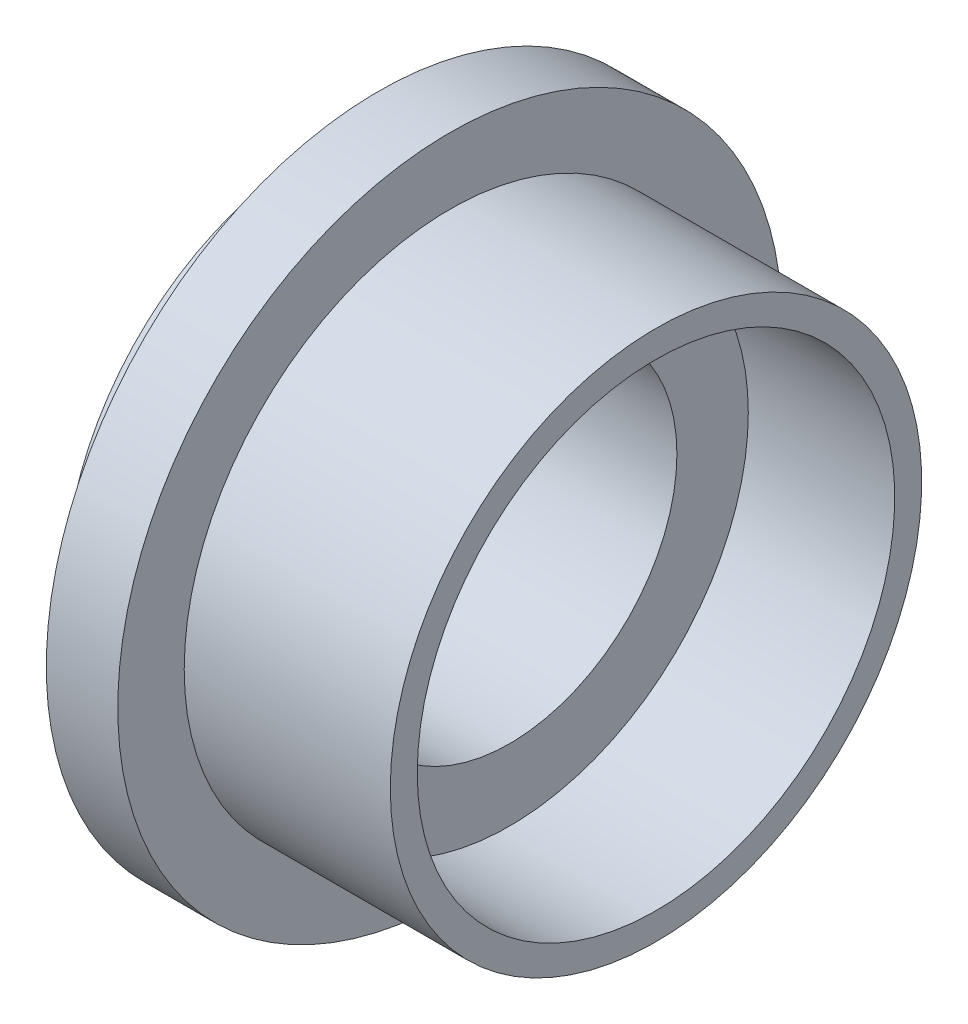
SolidWorks part; units mm, degrees
ref_plane "Front Plane" through (0, 0, 0) normal (0, 0, 1) x (1, 0, 0)
ref_plane "Top Plane" through (0, 0, 0) normal (0, 1, 0) x (1, 0, 0)
ref_plane "Right Plane" through (0, 0, 0) normal (1, 0, 0) x (0, 0, -1)
sketch "Sketch1" plane through (0, 0, 0) normal (0, 0, 1) x (1, 0, 0)
  line L0 (-3.5, 8) -> (-3.5, 11.412)
  line L1 (-3.5, 11.412) -> (-3.5, -9.888) construction
  line L2 (-3.5, 11.412) -> (-6.35, 11.412)
  line L3 (-6.35, 19.05) -> (-6.35, -19.05) construction
  line L4 (-6.35, 11.412) -> (-6.35, 15.875)
  line L5 (-6.35, 15.875) -> (-9.7671, 15.875)
  line L6 (-9.7671, 15.875) -> (-11.6001, 12.7)
  line L7 (-12.7, 12.065) -> (-22.904, 12.065) construction
  line L8 (-12.7, 12.065) -> (-12.7, 8)
  line L9 (-12.7, 8) -> (-3.5, 8)
  line L10 (0, 0) -> (-17.096, 0) construction
  arc A0 (-11.6001, 12.7) -> (-12.7, 12.065) centre (-12.7, 13.335) cw
  dimension "D1" = 15.875
  dimension "D3" = 1.27
  dimension "D2" = 8
  dimension "D4" = 6.35
  dimension "D5" = 60
  dimension "D6" = 3.81
revolve "Revolve1" add sketch "Sketch1" angle 360 about L10
sketch "Sketch2" plane through (-6.35, 0, 0) normal (1, 0, 0) x (0, 0, -1)
  circle A1 centre (0, 0) radius 12.7
  circle A2 centre (0, 0) radius 11.412
  circle A3 centre (0, 0) radius 11.412 construction
  dimension "D1" = 25.4
extrude "Boss-Extrude1" add sketch "Sketch2" along normal up to surface (9.85 mm away)
